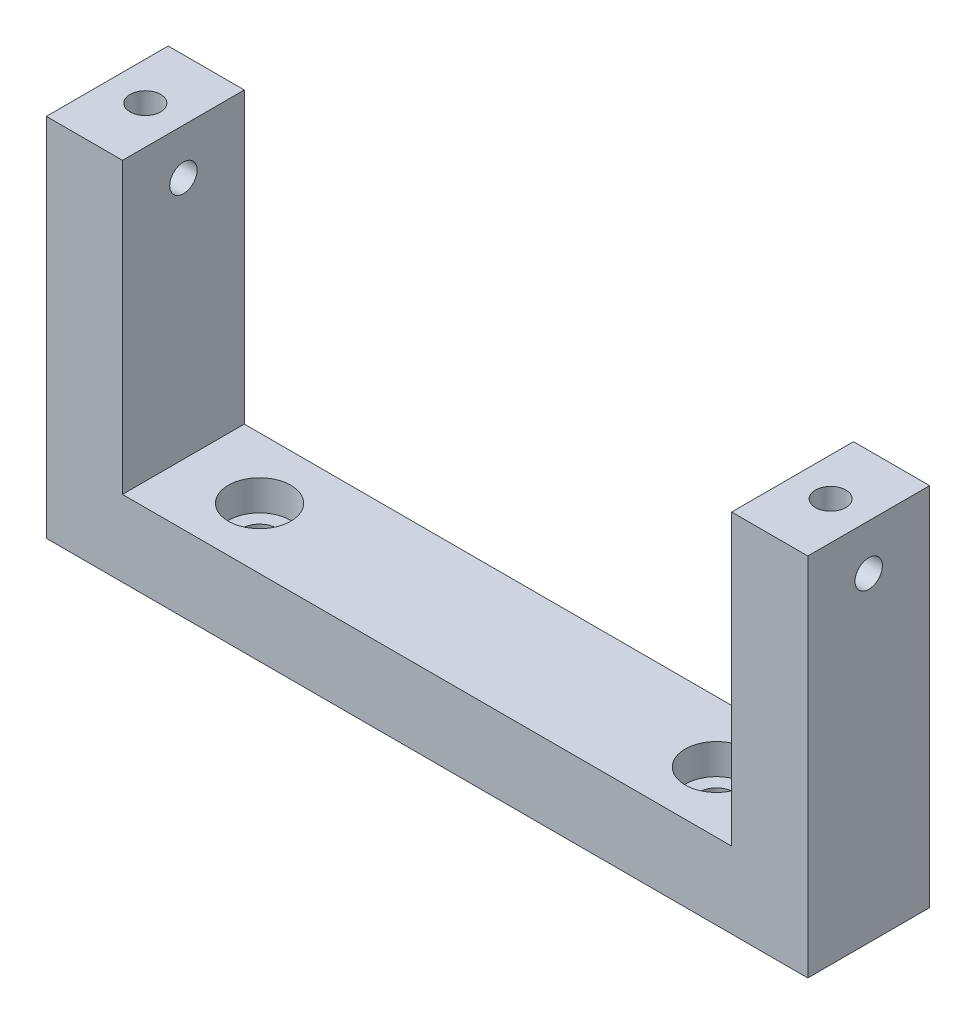
SolidWorks part; units mm, degrees
ref_plane "Front Plane" through (0, 0, 0) normal (0, 0, 1) x (1, 0, 0)
ref_plane "Top Plane" through (0, 0, 0) normal (0, 1, 0) x (1, 0, 0)
ref_plane "Right Plane" through (0, 0, 0) normal (1, 0, 0) x (0, 0, -1)
sketch "Sketch1" plane through (0, 0, 0) normal (0, 1, 0) x (1, 0, 0)
  line L1 (-25, -4) -> (25, -4)
  line L2 (-25, -4) -> (-25, 4)
  line L3 (-25, 4) -> (25, 4)
  line L4 (25, -4) -> (25, 4)
  line L5 (-25, -4) -> (25, 4) construction
  line L6 (-25, 4) -> (25, -4) construction
  point P0 (0, 0)
  dimension "D1" = 50
  dimension "D2" = 8
extrude "Boss-Extrude1" add sketch "Sketch1" along normal blind 5
sketch "Sketch5" plane through (25, 0, 0) normal (1, 0, 0) x (0, 0, -1)
  line L0 (0, 24) -> (0, 21) construction
  line L1 (-4, 0) -> (4, 0)
  line L2 (-4, 0) -> (-4, 24)
  line L3 (-4, 24) -> (4, 24)
  line L4 (4, 0) -> (4, 24)
  circle A0 centre (0, 21) radius 0.9
  dimension "D3" = 1.8
  dimension "D1" = 3
  dimension "D2" = 21
extrude "Boss-Extrude3" add sketch "Sketch5" against normal blind 5
sketch "Sketch6" plane through (0, 24, 0) normal (0, 1, 0) x (1, 0, 0)
  line L0 (20, 0) -> (25, 0) construction
  line L1 (20, 4) -> (20, -4) construction
  line L2 (25, 4) -> (25, -4) construction
  circle A0 centre (22.5, 0) radius 1
  dimension "D1" = 2
extrude "Cut-Extrude3" cut sketch "Sketch6" against normal up to next
sketch "Sketch2" plane through (0, 0, 0) normal (0, 1, 0) x (1, 0, 0)
  line L0 (0, 0) -> (15, 0) construction
  line L1 (0, 0) -> (0, 4) construction
  line L3 (20, 4) -> (-25, 4) construction
  circle A1 centre (15, 0) radius 1.15
  dimension "D1" = 2.3
  dimension "D3" = 30
extrude "Cut-Extrude1" cut sketch "Sketch2" along normal through all
sketch "Sketch7" plane through (0, 0, 0) normal (0, -1, 0) x (1, 0, 0)
  circle A1 centre (15, 0) radius 2.05
  dimension "D1" = 4.1
extrude "Cut-Extrude4" cut sketch "Sketch7" against normal up to next from offset 3 offset against normal yes
mirror "Mirror5" about plane through (0, 0, 0) normal (1, 0, 0) of "Cut-Extrude4", "Cut-Extrude1", "Cut-Extrude3", "Boss-Extrude3"
